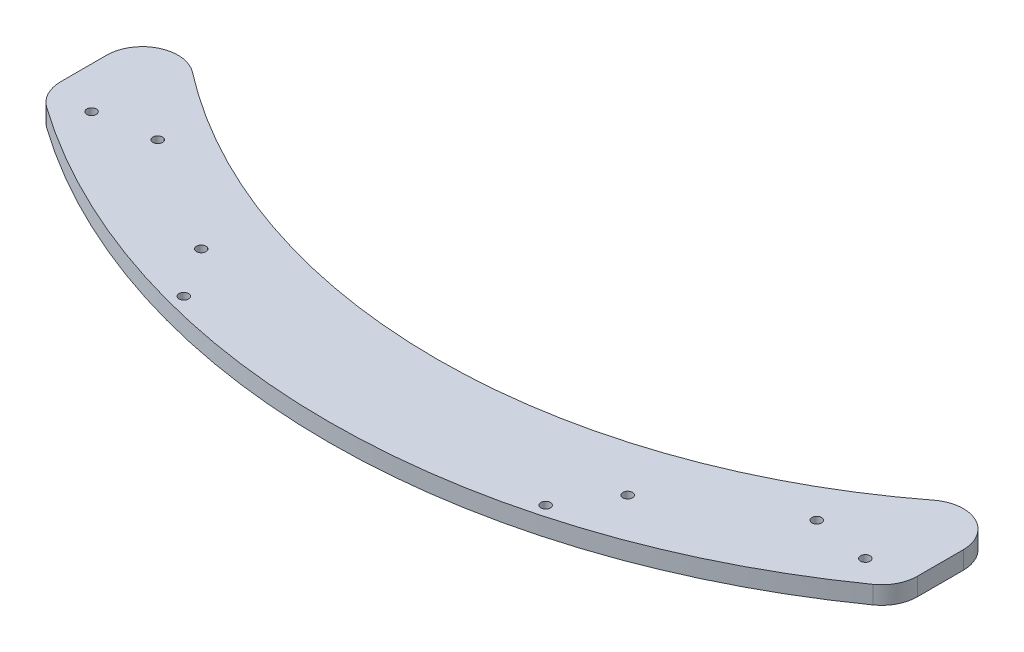
SolidWorks part; units mm, degrees
ref_plane "Front Plane" through (0, 0, 0) normal (0, 0, 1) x (1, 0, 0)
ref_plane "Top Plane" through (0, 0, 0) normal (0, 1, 0) x (1, 0, 0)
ref_plane "Right Plane" through (0, 0, 0) normal (1, 0, 0) x (0, 0, -1)
sketch "Sketch1" plane through (0, 0, 0) normal (0, 1, 0) x (1, 0, 0)
  line L0 (0, 0) -> (0, -152.4) construction
  line L1 (-152.4, -152.4) -> (152.4, -152.4) construction
  line L2 (-152.4, -152.4) -> (-152.4, 152.4) construction
  line L3 (-152.4, 152.4) -> (152.4, 152.4) construction
  line L4 (152.4, -152.4) -> (152.4, 152.4) construction
  line L5 (-152.4, -152.4) -> (152.4, 152.4) construction
  line L6 (-152.4, 152.4) -> (152.4, -152.4) construction
  line L7 (0, 0) -> (0, 102.2502) construction
  line L8 (0, 102.2502) -> (65.7158, 16.6077) construction
  line L9 (143.0285, -84.1481) -> (65.7158, 16.6077) construction
  line L10 (50.6024, 5.0108) -> (80.8292, 28.2047) construction
  line L11 (50.6024, 5.0108) -> (127.9151, -95.745) construction
  line L12 (127.9151, -95.745) -> (158.1419, -72.5512) construction
  line L13 (80.8292, 28.2047) -> (158.1419, -72.5512) construction
  line L14 (0, 102.2502) -> (50.1691, -133.7768) construction
  line L15 (50.1691, -133.7768) -> (68.8028, -129.8161) construction
  line L16 (68.8028, -129.8161) -> (42.398, -5.5913) construction
  line L17 (42.398, -5.5913) -> (5.1306, -13.5127) construction
  line L18 (5.1306, -13.5127) -> (31.5354, -137.7375) construction
  line L19 (31.5354, -137.7375) -> (50.1691, -133.7768) construction
  line L20 (0, 102.2502) -> (-65.7158, 16.6077) construction
  line L21 (-50.6024, 5.0108) -> (-80.8292, 28.2047) construction
  line L22 (-127.9151, -95.745) -> (-158.1419, -72.5512) construction
  line L23 (-80.8292, 28.2047) -> (-158.1419, -72.5512) construction
  line L24 (-50.6024, 5.0108) -> (-127.9151, -95.745) construction
  line L25 (-143.0285, -84.1481) -> (-65.7158, 16.6077) construction
  line L26 (-31.5354, -137.7375) -> (-50.1691, -133.7768) construction
  line L27 (-50.1691, -133.7768) -> (-68.8028, -129.8161) construction
  line L28 (-42.398, -5.5913) -> (-5.1306, -13.5127) construction
  line L29 (-5.1306, -13.5127) -> (-31.5354, -137.7375) construction
  line L30 (0, 102.2502) -> (-50.1691, -133.7768) construction
  line L31 (-68.8028, -129.8161) -> (-42.398, -5.5913) construction
  line L32 (0, 102.2502) -> (-152.4, -101.762) construction
  line L33 (0, 102.2502) -> (-112.0468, 18.8141) construction
  line L34 (0, 102.2502) -> (112.0468, 18.8141) construction
  line L35 (-105.9774, 26.7239) -> (-94.0975, 42.206) construction
  line L36 (94.0975, 42.206) -> (105.9774, 26.7239) construction
  line L37 (0, 102.2502) -> (152.4, -101.762) construction
  line L38 (-152.4, -50.962) -> (-152.4, -101.762) construction
  line L39 (152.4, -50.962) -> (152.4, -101.762) construction
  line L40 (72.5295, -129.0239) -> (45.3326, -1.0724) construction
  line L41 (45.3326, -1.0724) -> (0.6117, -10.5781) construction
  line L42 (0.6117, -10.5781) -> (27.8086, -138.5296) construction
  line L43 (81.5325, 33.5467) -> (161.1646, -70.2318) construction
  line L44 (45.2604, 5.7141) -> (81.5325, 33.5467) construction
  line L45 (45.2604, 5.7141) -> (124.8924, -98.0644) construction
  line L46 (98.1127, 11.939) -> (81.5325, 33.5467) construction
  line L47 (81.5325, 33.5467) -> (63.3964, 19.6304) construction
  line L48 (63.3964, 19.6304) -> (57.9845, 26.6833) construction
  line L49 (100.7298, 33.5626) -> (94.0975, 42.206) construction
  line L50 (91.0399, 21.1564) -> (81.5325, 33.5467) construction
  line L51 (81.5325, 33.5467) -> (63.3964, 19.6304) construction
  line L52 (54.7678, -6.6762) -> (45.2604, 5.7141) construction
  line L53 (45.2604, 5.7141) -> (63.3964, 19.6304) construction
  line L54 (47.2595, -10.1376) -> (45.3326, -1.0724) construction
  line L55 (45.3326, -1.0724) -> (0.6117, -10.5781) construction
  line L56 (-0.6117, -10.5781) -> (0.6117, -10.5781) construction
  line L57 (-100.7298, 33.5626) -> (-94.0975, 42.206) construction
  line L58 (-91.0399, 21.1564) -> (-81.5325, 33.5467) construction
  line L59 (-81.5325, 33.5467) -> (-63.3964, 19.6304) construction
  line L60 (-45.2604, 5.7141) -> (-63.3964, 19.6304) construction
  line L61 (-54.7678, -6.6762) -> (-45.2604, 5.7141) construction
  line L62 (-47.2595, -10.1376) -> (-45.3326, -1.0724) construction
  line L63 (-45.3326, -1.0724) -> (-0.6117, -10.5781) construction
  line L64 (-152.4, -78.9511) -> (-152.4, -95.2943) construction
  line L65 (152.4, -78.9511) -> (152.4, -95.2943) construction
  line L66 (47.5797, 2.6915) -> (127.2118, -101.0871) construction
  line L67 (127.2118, -101.0871) -> (160.4613, -75.5739) construction
  line L68 (125.4536, -114.4422) -> (145.6048, -98.9797) construction
  line L69 (145.6048, -98.9797) -> (139.8063, -91.423) construction
  line L70 (125.4536, -114.4422) -> (109.6045, -93.7873) construction
  line L71 (109.6045, -93.7873) -> (117.1612, -87.9888) construction
  line L72 (117.1612, -87.9888) -> (127.2118, -101.0871) construction
  line L73 (139.8063, -91.423) -> (127.2118, -101.0871) construction
  line L74 (127.9151, -95.745) -> (127.2118, -101.0871) construction
  line L75 (57.1725, -136.1833) -> (73.3217, -132.7507) construction
  line L76 (79.2059, -114.6211) -> (69.8891, -116.6014) construction
  line L77 (68.8028, -129.8161) -> (73.3217, -132.7507) construction
  line L78 (69.8891, -116.6014) -> (73.3217, -132.7507) construction
  line L79 (59.0208, -144.879) -> (57.1725, -136.1833) construction
  line L80 (84.4869, -139.466) -> (79.2059, -114.6211) construction
  line L81 (84.4869, -139.466) -> (59.0208, -144.879) construction
  line L82 (152.4, -78.9511) -> (152.4, -95.2943)
  line L83 (-152.4, -78.9511) -> (-152.4, -95.2943)
  circle A0 centre (0, 102.2502) radius 12.7 construction
  arc A1 (-147.0329, -105.6634) -> (147.0329, -105.6634) centre (0, 102.2502) ccw
  arc A2 (-131.9457, -68.8932) -> (131.9457, -68.8932) centre (0, 102.2502) ccw
  arc A3 (-105.492, 10.6668) -> (105.492, 10.6668) centre (0, 102.2502) ccw construction
  arc A4 (-74.137, 42.4484) -> (74.137, 42.4484) centre (0, 102.2502) ccw construction
  arc A5 (74.137, 42.4484) -> (94.0975, 42.206) centre (84.0219, 34.4748) cw construction
  arc A6 (-74.137, 42.4484) -> (-94.0975, 42.206) centre (-84.0219, 34.4748) ccw construction
  arc A7 (105.9774, 26.7239) -> (105.492, 10.6668) centre (95.9018, 18.9926) cw construction
  arc A8 (-105.9774, 26.7239) -> (-105.492, 10.6668) centre (-95.9018, 18.9926) ccw construction
  arc A9 (-97.8072, 11.6082) -> (110.1733, 27.1232) centre (0, 102.2502) ccw construction
  circle A10 centre (102.87, 17.3975) radius 1.7005 construction
  circle A11 centre (83.82, 40.64) radius 1.7005 construction
  circle A12 centre (25.4, 2.54) radius 1.7005 construction
  circle A13 centre (0, -30.48) radius 1.7005 construction
  circle A14 centre (-102.87, 17.3975) radius 1.7005 construction
  circle A15 centre (-83.82, 40.64) radius 1.7005 construction
  circle A16 centre (-25.4, 2.54) radius 1.7005 construction
  arc A17 (74.137, 42.4484) -> (-74.137, 42.4484) centre (0, 102.2502) cw construction
  arc A18 (-89.4237, 19.3775) -> (100.7298, 33.5626) centre (0, 102.2502) ccw construction
  arc A19 (91.0399, 21.1564) -> (100.7298, 33.5626) centre (0, 102.2502) ccw construction
  arc A20 (94.0975, 42.206) -> (74.137, 42.4484) centre (84.0219, 34.4748) ccw construction
  arc A21 (54.7678, -6.6762) -> (47.2595, -10.1376) centre (0, 102.2502) cw construction
  circle A22 centre (0, 0) radius 1.7005 construction
  circle A23 centre (-83.82, 40.64) radius 1.7005 construction
  arc A24 (-94.0975, 42.206) -> (-74.137, 42.4484) centre (-84.0219, 34.4748) cw construction
  arc A25 (-91.0399, 21.1564) -> (-100.7298, 33.5626) centre (0, 102.2502) cw construction
  arc A26 (-54.7678, -6.6762) -> (-47.2595, -10.1376) centre (0, 102.2502) ccw construction
  arc A27 (131.9457, -68.8932) -> (152.4, -78.9511) centre (139.7, -78.9511) cw
  arc A28 (152.4, -95.2943) -> (147.0329, -105.6634) centre (139.7, -95.2943) cw
  arc A29 (-147.0329, -105.6634) -> (-152.4, -95.2943) centre (-139.7, -95.2943) cw
  arc A30 (-131.9457, -68.8932) -> (-152.4, -78.9511) centre (-139.7, -78.9511) ccw
  circle A31 centre (117.2485, -95.9258) radius 1.7005
  circle A32 centre (137.6677, -99.067) radius 1.7005
  circle A33 centre (75.8677, -121.8225) radius 1.7005
  circle A34 centre (64.3739, -139.5215) radius 1.7005
  circle A35 centre (-117.2485, -95.9258) radius 1.7005
  circle A36 centre (-137.6677, -99.067) radius 1.7005
  circle A37 centre (-64.3739, -139.5215) radius 1.7005
  circle A38 centre (-75.8677, -121.8225) radius 1.7005
  point P0 (0, 0)
  point P60 (98.1127, 11.939)
  dimension "D4" = 25.4
  dimension "D19" = 12.7
  dimension "D13" = 139.7
  dimension "D14" = 95.25
  dimension "D18" = 12.7
  dimension "D21" = 133.35
  dimension "D22" = 3.4011
  dimension "D28" = 30.48
  dimension "D31" = 12.7
  dimension "D17" = 3.4011
  dimension "D38" = 3.4011
  dimension "D1" = 304.8
  dimension "D2" = 304.8
  dimension "D3" = 50.1498
  dimension "D5" = 127
  dimension "D6" = 38.1
  dimension "D7" = 37.5
  dimension "D8" = 107.95
  dimension "D9" = 12
  dimension "D10" = 38.1
  dimension "D11" = 127
  dimension "D12" = 114.3
  dimension "D15" = 19.05
  dimension "D16" = 50.8
  dimension "D20" = 3.81
  dimension "D23" = 102.87
  dimension "D24" = 83.82
  dimension "D25" = 40.64
  dimension "D26" = 25.4
  dimension "D27" = 2.54
  dimension "D30" = 11.8077
  dimension "D33" = 9.525
  dimension "D34" = 9.525
  dimension "D35" = 3.81
  dimension "D36" = 25.4
  dimension "D37" = 12.7
  dimension "D39" = 6.35
  dimension "D40" = 6.35
  dimension "D41" = 4.7625
  dimension "D42" = 4.7625
  dimension "D43" = 3.81
  dimension "D44" = 12.7
  dimension "D45" = 12.7
  dimension "D46" = 9.525
  dimension "D47" = 4.7625
  dimension "D48" = 6.35
  dimension "D49" = 6.35
  dimension "D50" = 4.7625
  dimension "D51" = 25.4
  dimension "D29" = 11.43
  dimension "D32" = 3.81
extrude "Boss-Extrude1" add sketch "Sketch1" along normal blind 6.35
